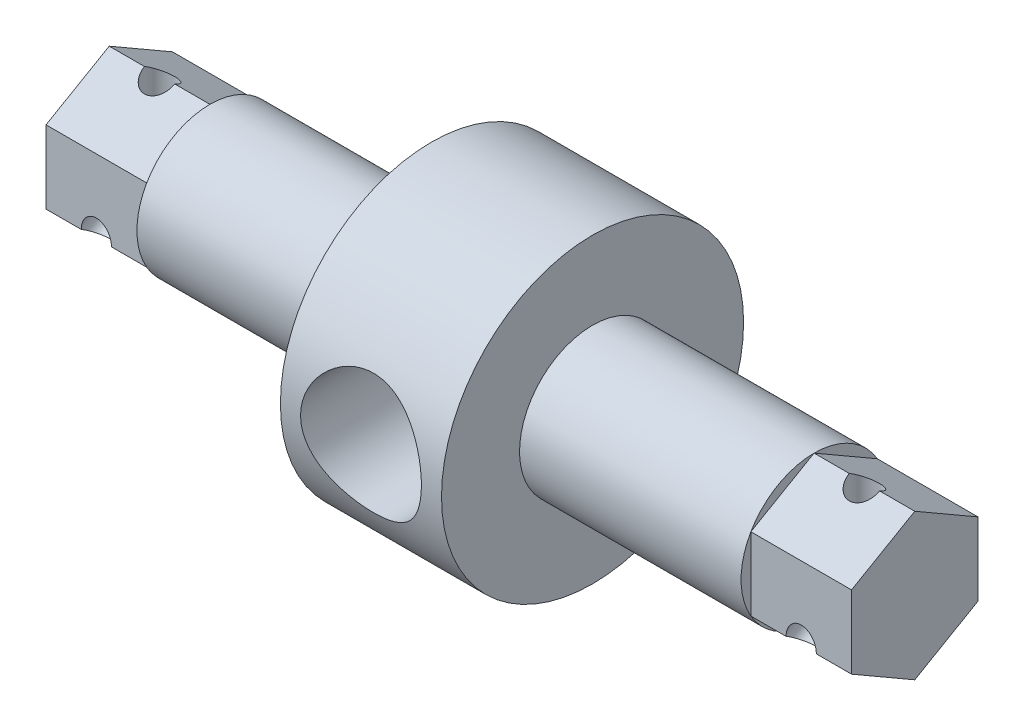
SolidWorks part; units mm, degrees
ref_plane "Front Plane" through (0, 0, 0) normal (0, 0, 1) x (1, 0, 0)
ref_plane "Top Plane" through (0, 0, 0) normal (0, 1, 0) x (1, 0, 0)
ref_plane "Right Plane" through (0, 0, 0) normal (1, 0, 0) x (0, 0, -1)
sketch "Sketch2" plane through (0, 0, 0) normal (1, 0, 0) x (0, 0, -1)
  circle A0 centre (0, 0) radius 7.5
  dimension "D1" = 7.5
extrude "Boss-Extrude1" add sketch "Sketch2" along normal mid plane 8
sketch "Sketch4" plane through (0, 0, 0) normal (1, 0, 0) x (0, 0, -1)
  circle A0 centre (0, 0) radius 3.625
  dimension "D1" = 7.25
extrude "Boss-Extrude3" add sketch "Sketch4" along normal mid plane 30
sketch "Sketch5" plane through (0, 0, 0) normal (-1, 0, 0) x (0, 0, 1)
  line L1 (0, 3.625) -> (-3.1393, 1.8125)
  line L2 (-3.1393, 1.8125) -> (-3.1393, -1.8125)
  line L3 (-3.1393, -1.8125) -> (0, -3.625)
  line L4 (0, -3.625) -> (3.1393, -1.8125)
  line L5 (3.1393, -1.8125) -> (3.1393, 1.8125)
  line L6 (3.1393, 1.8125) -> (0, 3.625)
  circle A0 centre (0, 0) radius 3.1393 construction
  circle A1 centre (0, 0) radius 3.625 construction
extrude "Boss-Extrude4" add sketch "Sketch5" along normal mid plane 40
sketch "Sketch1" plane through (0, 0, 0) normal (0, 0, 1) x (1, 0, 0)
  circle A0 centre (0, 0) radius 3
  dimension "D1" = 3
extrude "Cut-Extrude1" cut sketch "Sketch1" against normal through all both and the other way through all
ref_plane "Plane1" through (0, 3.625, 0) normal (0, 1, 0) x (1, 0, 0)
sketch "Sketch6" plane through (0, 3.625, -26.1154) normal (0, -1, 0) x (-1, 0, 0)
  line L0 (20, -26.1154) -> (15, -26.1154) construction
  circle A0 centre (17.5, -26.1154) radius 0.75
  dimension "D1" = 0.75
extrude "Cut-Extrude2" cut sketch "Sketch6" along normal blind 2
pattern_circular "CirPattern1" count 3 over 360 about axis through (0, 0, 0) along (1, 0, 0) of "Cut-Extrude2"
mirror "Mirror1" about plane through (0, 0, 0) normal (1, 0, 0) of "Cut-Extrude2", "CirPattern1"
